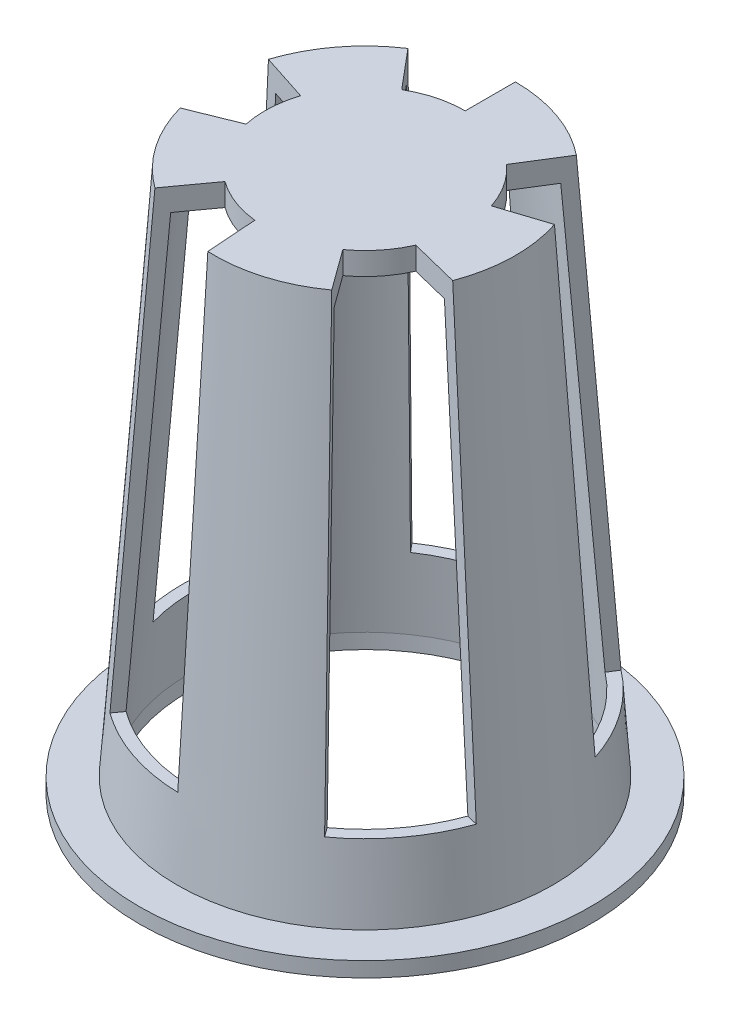
SolidWorks part; units mm, degrees
ref_plane "Front Plane" through (0, 0, 0) normal (0, 0, 1) x (1, 0, 0)
ref_plane "Top Plane" through (0, 0, 0) normal (0, 1, 0) x (1, 0, 0)
ref_plane "Right Plane" through (0, 0, 0) normal (1, 0, 0) x (0, 0, -1)
sketch "Sketch4" plane through (0, 0, 0) normal (0, 1, 0) x (1, 0, 0)
  circle A0 centre (0, 0) radius 25
  dimension "D1" = 50
sketch "Sketch5" plane through (0, 0, 0) normal (1, 0, 0) x (0, 0, -1)
  line L0 (0, 0) -> (0, 70)
  dimension "D1" = 70
ref_plane "Plane1" through (0, 70, 0) normal (0, 1, 0) x (1, 0, 0)
sketch "Sketch6" plane through (0, 70, 0) normal (0, 1, 0) x (1, 0, 0)
  circle A0 centre (0, 0) radius 20
  dimension "D1" = 40
loft "Loft1" add profiles "Sketch6", "Sketch4"
sketch "Sketch7" plane through (0, 0, 0) normal (0, -1, 0) x (1, 0, 0)
  circle A0 centre (0, 0) radius 23.5
  dimension "D1" = 47
ref_plane "Plane2" through (0, 67, 0) normal (0, 1, 0) x (1, 0, 0)
sketch "Sketch8" plane through (0, 67, 0) normal (0, 1, 0) x (1, 0, 0)
  circle A0 centre (0, 0) radius 18.5
  dimension "D1" = 37
loft "Cut-Loft2" cut profiles "Sketch8", "Sketch7"
sketch "Sketch9" plane through (0, 0, 0) normal (0, 1, 0) x (1, 0, 0)
  circle A0 centre (0, 0) radius 30
  dimension "D1" = 60
extrude "Boss-Extrude1" add sketch "Sketch9" against normal blind 2
sketch "Sketch10" plane through (0, -2, 0) normal (0, -1, 0) x (1, 0, 0)
  circle A0 centre (0, 0) radius 23.5
  dimension "D1" = 47
extrude "Cut-Extrude2" cut sketch "Sketch10" against normal blind 2
sketch "Sketch11" plane through (0, 70, 0) normal (0, 1, 0) x (1, 0, 0)
  line L12 (0, 13.334) -> (0, 25)
  line L13 (-6.667, 11.5476) -> (-14.2269, 20.5571)
  line L14 (12.6814, 4.1204) -> (23.7764, 7.7254)
  line L15 (8.9222, 9.9091) -> (15.1546, 19.8831)
  line L16 (7.8375, -10.7874) -> (14.6946, -20.2254)
  line L17 (12.1812, -5.4234) -> (23.593, -8.2687)
  line L18 (-7.8375, -10.7874) -> (-14.6946, -20.2254)
  line L19 (-1.3938, -13.261) -> (-0.5734, -24.9934)
  line L20 (-12.6814, 4.1204) -> (-23.7764, 7.7254)
  line L21 (-13.0426, -2.7723) -> (-23.9473, -7.1781)
  circle A11 centre (0, 0) radius 25 construction
  arc A12 (-14.2269, 20.5571) -> (0, 25) centre (0, 0) cw
  arc A13 (15.1546, 19.8831) -> (23.7764, 7.7254) centre (0, 0) cw
  arc A14 (23.593, -8.2687) -> (14.6946, -20.2254) centre (0, 0) cw
  arc A15 (-0.5734, -24.9934) -> (-14.6946, -20.2254) centre (0, 0) cw
  arc A16 (-23.9473, -7.1781) -> (-23.7764, 7.7254) centre (0, 0) cw
  arc A17 (-7.8375, -10.7874) -> (-1.3938, -13.261) centre (0, 0) ccw
  arc A18 (0, 13.334) -> (-6.667, 11.5476) centre (0, 0) ccw
  arc A19 (-12.6814, 4.1204) -> (-13.0426, -2.7723) centre (0, 0) ccw
  arc A20 (12.6814, 4.1204) -> (8.9222, 9.9091) centre (0, 0) ccw
  arc A21 (7.8375, -10.7874) -> (12.1812, -5.4234) centre (0, 0) ccw
  point P22 (0, 0)
  dimension "D1" = 40
extrude "Cut-Extrude4" cut sketch "Sketch11" against normal blind 60
